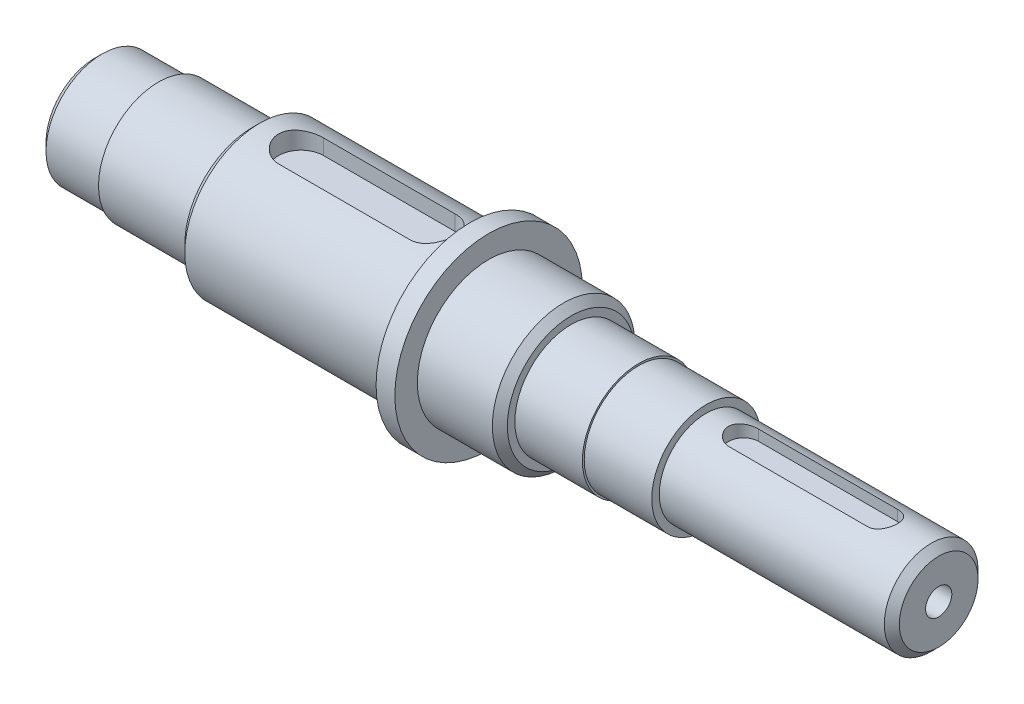
SolidWorks part; units mm, degrees
material "AISI 4340 Çelik, tavlı"
ref_plane "Ön Düzlem" through (0, 0, 0) normal (0, 0, 1) x (1, 0, 0)
ref_plane "Üst Düzlem" through (0, 0, 0) normal (0, 1, 0) x (1, 0, 0)
ref_plane "Sağ Düzlem" through (0, 0, 0) normal (1, 0, 0) x (0, 0, -1)
sketch "Çizim1" plane through (0, 0, 0) normal (0, 0, -1) x (1, 0, 0)
  line L0 (0, 0) -> (225, 0)
  line L1 (0, 0) -> (0, 15)
  line L2 (0, 15) -> (17, 15)
  line L3 (17, 15) -> (17, 16)
  line L4 (17, 16) -> (42, 16)
  line L5 (42, 16) -> (42, 20)
  line L6 (42, 20) -> (100, 20)
  line L7 (100, 20) -> (100, 25)
  line L8 (100, 25) -> (105, 25)
  line L9 (105, 25) -> (105, 19)
  line L10 (105, 19) -> (127, 19)
  line L11 (127, 19) -> (127, 15)
  line L12 (127, 15) -> (145, 15)
  line L13 (145, 15) -> (145, 14.5)
  line L14 (145, 14.5) -> (163, 14.5)
  line L15 (163, 14.5) -> (163, 12.5)
  line L16 (163, 12.5) -> (225, 12.5)
  line L17 (225, 12.5) -> (225, 0)
  dimension "D1" = 17
  dimension "D2" = 58
  dimension "D3" = 25
  dimension "D4" = 5
  dimension "D5" = 62
  dimension "D6" = 18
  dimension "D7" = 18
  dimension "D8" = 22
  dimension "D9" = 15
  dimension "D10" = 16
  dimension "D11" = 20
  dimension "D12" = 25
  dimension "D13" = 19
  dimension "D14" = 15
  dimension "D15" = 14.5
  dimension "D16" = 12.5
revolve "Döndür1" add sketch "Çizim1" angle 360 about L0
chamfer "Pah1" distance 2 angle 45 4 edges at (225, 0, 12.5) (127, 0, 19) (0, 0, 15) (42, 0, 20)
sketch "Çizim2" plane through (0, 0, 0) normal (0, 1, 0) x (1, 0, 0)
  line L0 (55, 0) -> (90, 0) construction
  line L1 (55, 6) -> (90, 6)
  line L2 (55, -6) -> (90, -6)
  line L3 (100, 25) -> (100, -25) construction
  arc A0 (55, 6) -> (55, -6) centre (55, 0) ccw
  arc A1 (90, -6) -> (90, 6) centre (90, 0) ccw
  point P2 (72.5, 0)
  dimension "D1" = 6
  dimension "D3" = 10
  dimension "D2" = 35
extrude "Kes-Ekstrüzyon1" cut sketch "Çizim2" along normal blind 10 from offset 15
sketch "Çizim3" plane through (0, 0, 0) normal (0, 1, 0) x (1, 0, 0)
  line L0 (173, 0) -> (210, 0) construction
  line L1 (173, 4) -> (210, 4)
  line L2 (173, -4) -> (210, -4)
  line L3 (225, -10.5) -> (225, 10.5) construction
  arc A0 (173, 4) -> (173, -4) centre (173, 0) ccw
  arc A1 (210, -4) -> (210, 4) centre (210, 0) ccw
  point P2 (191.5, 0)
  dimension "D1" = 4
  dimension "D3" = 15
  dimension "D2" = 37
extrude "Kes-Ekstrüzyon2" cut sketch "Çizim3" along normal blind 10 from offset 9
hole_wizard "M8x1.0 Dişli Delik1" positions "Çizim4" profile "Çizim6" tap size "M8x1.0" standard "ANSI Metrik"
sketch "Çizim4" plane through (225, 0, 0) normal (1, 0, 0) x (0, 0, -1)
  point P0 (0, 0)
sketch "Çizim6" plane through (225, 0, 0) normal (0, 1, 0) x (0, 0, -1)
  line L0 (0, 0) -> (0, 30.103)
  line L1 (0, 30.103) -> (3.5, 28)
  line L2 (3.5, 28) -> (3.5, 0)
  line L5 (3.5, 0) -> (0, 0)
  line L10 (0, 30.103) -> (-3.5, 28) construction
  line L11 (0, -6.35) -> (0, 107.95) construction
  dimension "Tap Drill Dia." = 7
  dimension "Tap Drill Depth" = 28
  dimension "Drill Angle" = 118
cosmetic thread "Delik Dişi1" parameters "D1"=25, "D2"=8
hole_wizard "M10x1.25 Dişli Delik1" positions "Çizim7" profile "Çizim8" tap size "M10x1.25" standard "ANSI Metrik"
sketch "Çizim7" plane through (0, 0, 0) normal (-1, 0, 0) x (0, 0, 1)
  point P0 (0, 0)
sketch "Çizim8" plane through (0, 0, 0) normal (0, 1, 0) x (0, 0, 1)
  line L0 (0, 0) -> (0, 31.3938)
  line L1 (0, 31.3938) -> (4.4, 28.75)
  line L2 (4.4, 28.75) -> (4.4, 0)
  line L5 (4.4, 0) -> (0, 0)
  line L10 (0, 31.3938) -> (-4.4, 28.75) construction
  line L11 (0, -6.35) -> (0, 107.95) construction
  dimension "Tap Drill Dia." = 8.8
  dimension "Tap Drill Depth" = 28.75
  dimension "Drill Angle" = 118
cosmetic thread "Delik Dişi2" parameters "D1"=25, "D2"=10
